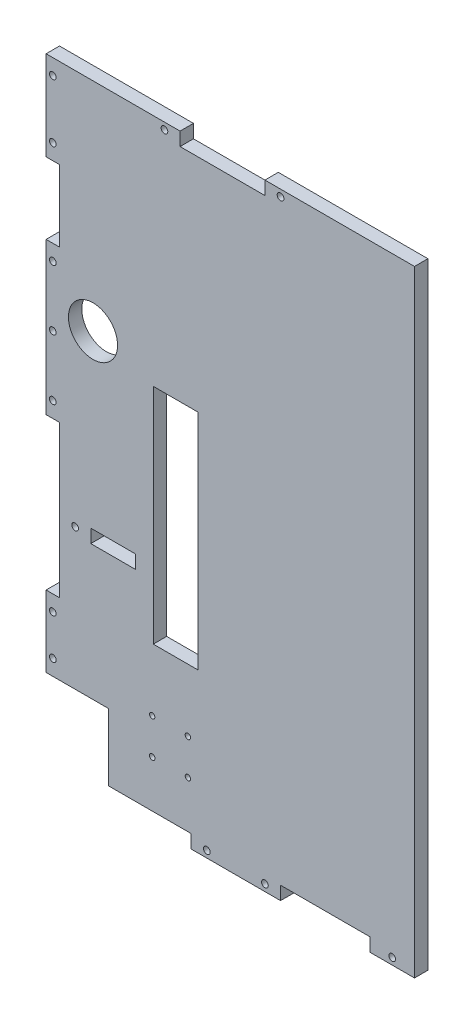
SolidWorks part; units mm, degrees
ref_plane "Plan de face" through (0, 0, 0) normal (0, 0, 1) x (1, 0, 0)
ref_plane "Plan de dessus" through (0, 0, 0) normal (0, 1, 0) x (1, 0, 0)
ref_plane "Plan de droite" through (0, 0, 0) normal (1, 0, 0) x (0, 0, -1)
sketch "Esquisse1" plane through (0, 0, 0) normal (0, 0, 1) x (1, 0, 0)
  line L1 (0, 0) -> (-165, 0)
  line L2 (0, 0) -> (0, 276)
  line L3 (0, 276) -> (-165, 276)
  line L4 (-165, 0) -> (-165, 276)
  dimension "D1" = 276
  dimension "D2" = 165
extrude "Boss.-Extru.1" add sketch "Esquisse1" along normal blind 6
sketch "Esquisse2" plane through (0, 0, 6) normal (0, 0, 1) x (1, 0, 0)
  line L0 (0, 276) -> (-165, 276) construction
  line L8 (0, 276) -> (-165, 276) construction
  line L9 (-165, 0) -> (0, 0) construction
  line L10 (-105, 276) -> (-67, 276)
  line L11 (-105, 276) -> (-105, 270)
  line L12 (-105, 270) -> (-67, 270)
  line L13 (-165, 276) -> (-165, 0) construction
  line L14 (-165, 236) -> (-159, 236)
  line L15 (-165, 236) -> (-165, 204)
  line L16 (-165, 204) -> (-159, 204)
  line L17 (-159, 236) -> (-159, 204)
  line L19 (-165, 136) -> (-159, 136)
  line L20 (-165, 136) -> (-165, 68)
  line L21 (-165, 68) -> (-159, 68)
  line L22 (-159, 136) -> (-159, 68)
  line L23 (-137, 36) -> (-137, 6)
  line L24 (-165, 0) -> (-165, 36)
  line L25 (-165, 36) -> (-137, 36)
  line L26 (-100, 0) -> (-165, 0)
  line L27 (-20, 0) -> (-60, 0)
  line L28 (-20, 0) -> (-20, 6)
  line L29 (-20, 6) -> (-60, 6)
  line L30 (-60, 0) -> (-60, 6)
  line L31 (0, 0) -> (0, 276) construction
  line L33 (-100, 0) -> (-100, 6)
  line L34 (-100, 6) -> (-137, 6)
  line L35 (-67, 276) -> (-67, 270)
  dimension "D1" = 6
  dimension "D2" = 6
  dimension "D3" = 68
  dimension "D4" = 32
  dimension "D5" = 40
  dimension "D6" = 68
  dimension "D7" = 36
  dimension "D8" = 28
  dimension "D9" = 6
  dimension "D10" = 40
  dimension "D11" = 6
  dimension "D12" = 40
  dimension "D13" = 20
  dimension "D14" = 38
  dimension "D15" = 60
  dimension "D16" = 6
extrude "exterieur" cut sketch "Esquisse2" against normal blind 10
sketch "Esquisse3" plane through (0, 0, 6) normal (0, 0, 1) x (1, 0, 0)
  line L0 (-165, 204) -> (-159, 204) construction
  line L1 (-145, 102) -> (-125, 102)
  line L2 (-145, 102) -> (-145, 96)
  line L3 (-145, 96) -> (-125, 96)
  line L4 (-125, 102) -> (-125, 96)
  line L5 (-165, 204) -> (-165, 136) construction
  line L6 (-165, 68) -> (-165, 36) construction
  line L8 (-100, 0) -> (-60, 0) construction
  circle A0 centre (-144, 178.92) radius 11
  dimension "D1" = 22
  dimension "D2" = 20
  dimension "D4" = 21
  dimension "D3" = 6
  dimension "D5" = 25.08
  dimension "D6" = 20
  dimension "D7" = 102
extrude "Enlèv. mat.-Extru.2" cut sketch "Esquisse3" against normal through all
sketch "Esquisse4" plane through (0, 0, 6) normal (0, 0, 1) x (1, 0, 0)
  line L0 (-105, 270) -> (-67, 270) construction
  line L1 (-105, 276) -> (-165, 276) construction
  line L2 (-105, 276) -> (-105, 270) construction
  line L3 (-67, 270) -> (-67, 276) construction
  line L4 (-165, 204) -> (-159, 204) construction
  line L5 (-159, 136) -> (-165, 136) construction
  line L6 (-165, 68) -> (-159, 68) construction
  line L7 (-137, 36) -> (-165, 36) construction
  line L8 (-100, 0) -> (-100, 6) construction
  line L9 (-60, 6) -> (-60, 0) construction
  line L10 (-100, 0) -> (-60, 0) construction
  line L11 (-165, 68) -> (-165, 36) construction
  line L12 (-165, 204) -> (-165, 136) construction
  line L13 (-20, 0) -> (0, 0) construction
  line L14 (-20, 0) -> (-20, 6) construction
  line L15 (-165, 276) -> (-165, 236) construction
  line L16 (-159, 236) -> (-165, 236) construction
  line L17 (-145, 102) -> (-145, 96) construction
  line L18 (-145, 96) -> (-125, 96) construction
  line L19 (-100, 6) -> (-137, 6) construction
  line L20 (-137, 6) -> (-137, 36) construction
  circle A0 centre (-60, 273) radius 1.5
  circle A1 centre (-112, 273) radius 1.5
  circle A2 centre (-162, 197) radius 1.5
  circle A3 centre (-162, 170) radius 1.5
  circle A4 centre (-162, 143) radius 1.5
  circle A5 centre (-162, 61) radius 1.5
  circle A6 centre (-162, 43) radius 1.5
  circle A7 centre (-93, 3) radius 1.5
  circle A8 centre (-67, 3) radius 1.5
  circle A9 centre (-10, 3) radius 1.5
  circle A10 centre (-162, 269) radius 1.5
  circle A11 centre (-162, 243) radius 1.5
  circle A12 centre (-117.5, 27) radius 1.2528
  circle A13 centre (-117.5, 43) radius 1.193
  circle A14 centre (-101.5, 43) radius 1.2267
  circle A15 centre (-101.5, 27) radius 1.1856
  circle A16 centre (-152, 99) radius 1.5
  point P28 (-162, 204)
  point P45 (-165, 170)
  point P46 (-10, 0)
  point P49 (-20, 3)
  point P60 (-162, 236)
  point P81 (-118.5, 6)
  dimension "D1" = 3
  dimension "D2" = 3
  dimension "D3" = 3
  dimension "D4" = 7
  dimension "D5" = 3
  dimension "D6" = 7
  dimension "D7" = 3
  dimension "D8" = 7
  dimension "D9" = 3
  dimension "D10" = 34
  dimension "D11" = 3
  dimension "D12" = 7
  dimension "D13" = 3
  dimension "D14" = 7
  dimension "D15" = 3
  dimension "D16" = 7
  dimension "D17" = 3
  dimension "D18" = 3
  dimension "D19" = 7
  dimension "D20" = 7
  dimension "D21" = 3
  dimension "D22" = 3
  dimension "D23" = 3
  dimension "D24" = 3
  dimension "D25" = 3
  dimension "D26" = 3
  dimension "D27" = 3
  dimension "D28" = 3
  dimension "D29" = 3
  dimension "D30" = 10
  dimension "D31" = 3
  dimension "D32" = 3
  dimension "D33" = 7
  dimension "D34" = 3
  dimension "D35" = 7
  dimension "D36" = 3
  dimension "D37" = 3
  dimension "D38" = 7
  dimension "D39" = 3
  dimension "D40" = 16
  dimension "D41" = 16
  dimension "D42" = 16
  dimension "D43" = 21
  dimension "D44" = 19.5
extrude "Enlèv. mat.-Extru.3" cut sketch "Esquisse4" against normal through all
sketch "Esquisse5" plane through (0, 0, 0) normal (0, 0, -1) x (-1, 0, 0)
  circle A0 centre (60, 273) radius 2.995
  circle A1 centre (112, 273) radius 2.995
  circle A2 centre (162, 197) radius 2.995
  circle A3 centre (162, 170) radius 2.995
  circle A4 centre (162, 143) radius 2.995
  circle A5 centre (162, 61) radius 2.995
  circle A6 centre (162, 43) radius 2.995
  circle A7 centre (93, 3) radius 2.995
  circle A8 centre (67, 3) radius 2.995
  circle A9 centre (10, 3) radius 2.995
  circle A10 centre (162, 269) radius 2.995
  circle A11 centre (162, 243) radius 2.995
  circle A12 centre (152, 99) radius 3
  circle A13 centre (117.5, 43) radius 2
  circle A14 centre (117.5, 27) radius 2
  circle A15 centre (101.5, 27) radius 2
  circle A16 centre (101.5, 43) radius 2
  dimension "D1" = 5.99
  dimension "D2" = 5.99
  dimension "D3" = 5.99
  dimension "D4" = 5.99
  dimension "D5" = 5.99
  dimension "D6" = 5.99
  dimension "D7" = 5.99
  dimension "D8" = 5.99
  dimension "D9" = 5.99
  dimension "D10" = 5.99
  dimension "D11" = 5.99
  dimension "D12" = 5.99
  dimension "D13" = 4
  dimension "D14" = 4
  dimension "D15" = 4
  dimension "D16" = 4
  dimension "D17" = 6
extrude "Enlèv. mat.-Extru.4" cut sketch "Esquisse5" against normal blind 3
sketch "Esquisse6" plane through (0, 0, 0) normal (0, 0, -1) x (-1, 0, 0)
  line L0 (165, 204) -> (165, 136) construction
  line L1 (97, 171) -> (117, 171)
  line L2 (97, 171) -> (97, 71)
  line L3 (97, 71) -> (117, 71)
  line L4 (117, 171) -> (117, 71)
  line L5 (100, 6) -> (137, 6) construction
  dimension "D1" = 20
  dimension "D2" = 48
  dimension "D3" = 65
  dimension "D4" = 100
extrude "Enlèv. mat.-Extru.5" cut sketch "Esquisse6" against normal through all
